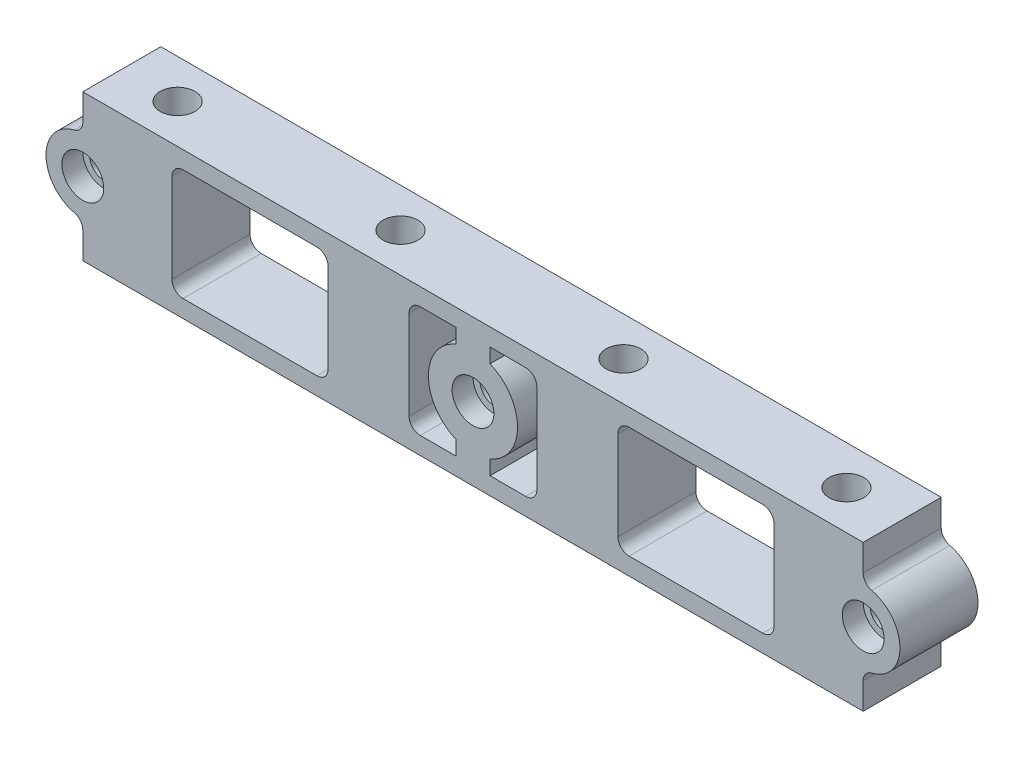
SolidWorks part; units mm, degrees
material "7075-T6 (SN)"
ref_plane "X-Y Datum" through (0, 0, 0) normal (0, 0, 1) x (1, 0, 0)
ref_plane "X-Z Datum" through (0, 0, 0) normal (0, 1, 0) x (1, 0, 0)
ref_plane "Y-Z Datum" through (0, 0, 0) normal (1, 0, 0) x (0, 0, -1)
other "Graphic1"
other "Graphic (Closed) -1"
other "Graphic2"
other "Graphic (Closed) -2"
other "Graphic3"
other "Graphic (Closed) -3"
sketch "Sketch1" plane through (0, 0, 0) normal (0, 0, 1) x (1, 0, 0)
  line L1 (8.7312, 16.6687) -> (-186.5312, 16.6687)
  line L5 (-8.7312, 0) -> (0, 0) construction
  line L7 (-186.5312, -16.6687) -> (-186.5312, 16.6687)
  line L8 (-8.7312, 0) -> (-16.6687, 0) construction
  line L9 (-8.7312, 0) -> (-8.7312, 16.6687) construction
  line L10 (-8.7312, 16.6687) -> (-16.6688, 16.6687) construction
  line L11 (-16.6687, 0) -> (-16.6688, 16.6687) construction
  line L12 (-67.4688, 0) -> (-59.5313, 0) construction
  line L13 (-67.4688, 0) -> (-67.4688, 16.6687) construction
  line L14 (-67.4688, 16.6687) -> (-59.5313, 16.6687) construction
  line L15 (-59.5313, 0) -> (-59.5313, 16.6687) construction
  line L17 (-186.5312, -16.6687) -> (8.7312, -16.6687)
  line L19 (8.7312, -16.6687) -> (8.7312, 16.6687)
  line L20 (-110.3313, 16.6687) -> (-118.2687, 16.6687) construction
  line L21 (-110.3313, 16.6687) -> (-110.3313, 0) construction
  line L22 (-110.3313, 0) -> (-118.2687, 0) construction
  line L23 (-118.2687, 16.6687) -> (-118.2687, 0) construction
  line L24 (-161.1313, 16.6687) -> (-169.0688, 16.6687) construction
  line L25 (-161.1313, 16.6687) -> (-161.1313, 0) construction
  line L26 (-161.1313, 0) -> (-169.0688, 0) construction
  line L27 (-169.0688, 16.6687) -> (-169.0688, 0) construction
  line L28 (0, 0) -> (8.7312, 0) construction
  line L29 (-177.8, 0) -> (-186.5312, 0) construction
  circle A0 centre (0, 0) radius 3.175
  circle A4 centre (-177.8, 0) radius 3.175
  circle A6 centre (-88.9, 0) radius 3.175
  point P1 (-186.5312, 0)
  point P22 (-12.7, 0)
  point P23 (-63.5, 0)
  point P31 (-114.3, 0)
  point P32 (-165.1, 0)
  point P38 (-88.9, -16.6687)
  dimension "D2" = 6.35
  dimension "D3" = 12.7
  dimension "D1" = 50.8
  dimension "D4" = 12.7
  dimension "D6" = 7.9375
  dimension "D7" = 7.9375
  dimension "D8" = 33.3375
  dimension "D11" = 50.8
  dimension "D12" = 50.8
extrude "Boss-Extrude1" add sketch "Sketch1" against normal blind 17.78
ref_plane "Plane1" through (0, 0, 0) normal (0, -1, 0) x (-1, 0, 0)
sketch "Sketch2" plane through (0, 16.6687, 0) normal (0, 1, 0) x (1, 0, 0)
  line L0 (-186.5312, 0) -> (8.7313, 0) construction
  line L4 (0, 0) -> (0, 17.78) construction
  line L5 (8.7313, 17.78) -> (-186.5312, 17.78) construction
  circle A0 centre (-12.7, 8.89) radius 3.9688
  circle A2 centre (-63.5, 8.89) radius 3.9688
  circle A3 centre (-114.3, 8.89) radius 3.9687
  circle A4 centre (-165.1, 8.89) radius 3.9688
  dimension "D2" = 7.9375
  dimension "D1" = 4
  dimension "D3" = 8.89
  dimension "D4" = 12.7
  dimension "D5" = 50.8
extrude "Cut-Extrude1" cut sketch "Sketch2" against normal up to surface (33.3375 mm away) up to face at (-88.9, -16.6687, -8.89)
sketch "Sketch3" plane through (0, 0, 0) normal (0, 0, 1) x (1, 0, 0)
  circle A0 centre (0, 0) radius 4.7625
  circle A1 centre (-88.9, 0) radius 4.7625
  circle A2 centre (-177.8, 0) radius 4.7625
  circle A3 centre (-177.8, 0) radius 3.175 construction
  dimension "D1" = 9.525
extrude "Cut-Extrude2" cut sketch "Sketch3" against normal blind 4.7752
ref_point "Point1"
ref_point "Point2"
ref_point "Point3"
ref_point "Point4"
sketch "Sketch5" plane through (0, 0, 0) normal (0, 0, 1) x (1, 0, 0)
  line L0 (0, -16.6687) -> (8.7312, -16.6687)
  line L1 (0, -10.6225) -> (0, -16.6687)
  line L2 (-186.5312, -16.6687) -> (8.7312, -16.6687) construction
  line L3 (0, 10.6225) -> (0, 16.6687)
  line L4 (8.7312, 16.6687) -> (-186.5312, 16.6687) construction
  line L5 (8.7312, -16.6687) -> (8.7312, 16.6687)
  line L6 (8.7312, 16.6687) -> (0, 16.6687)
  line L7 (-88.9, -16.6687) -> (-88.9, 16.6687) construction
  line L8 (0, 0) -> (-20.32, 0) construction
  line L9 (-22.86, -12.7) -> (-53.34, -12.7)
  line L10 (-20.32, -10.16) -> (-20.32, 10.16)
  line L11 (-22.86, 12.7) -> (-53.34, 12.7)
  line L12 (-55.88, -10.16) -> (-55.88, 10.16)
  line L13 (-85.0119, -9.3866) -> (-85.0119, -12.7)
  line L14 (-85.0119, -12.7) -> (-76.8839, -12.7)
  line L15 (-74.3439, -10.16) -> (-74.3439, 10.16)
  line L16 (-76.8839, 12.7) -> (-85.0119, 12.7)
  line L17 (-85.0119, 12.7) -> (-85.0119, 9.3866)
  line L18 (-88.9, 0) -> (-85.0119, -9.3866) construction
  line L19 (-88.9, 0) -> (-85.0119, 9.3866) construction
  line L20 (-100.9161, 12.7) -> (-92.7881, 12.7)
  line L21 (-103.4561, -10.16) -> (-103.4561, 10.16)
  line L22 (-92.7881, -12.7) -> (-100.9161, -12.7)
  line L23 (-92.7881, -9.3866) -> (-92.7881, -12.7)
  line L24 (-92.7881, 12.7) -> (-92.7881, 9.3866)
  line L25 (-154.94, 12.7) -> (-124.46, 12.7)
  line L26 (-121.92, -10.16) -> (-121.92, 10.16)
  line L27 (-154.94, -12.7) -> (-124.46, -12.7)
  line L28 (-157.48, -10.16) -> (-157.48, 10.16)
  line L29 (-186.5312, -16.6687) -> (-186.5312, 16.6687)
  line L30 (-177.8, -16.6687) -> (-186.5312, -16.6687)
  line L31 (-177.8, -10.6225) -> (-177.8, -16.6687)
  line L32 (-177.8, 10.6225) -> (-177.8, 16.6687)
  line L33 (-186.5312, 16.6687) -> (-177.8, 16.6687)
  arc A0 (1.9493, 8.1522) -> (1.9493, -8.1522) centre (0, 0) cw
  arc A1 (-85.0119, -9.3866) -> (-85.0119, 9.3866) centre (-88.9, 0) ccw
  arc A2 (0, -10.6225) -> (1.9493, -8.1522) centre (2.54, -10.6225) cw
  arc A3 (-22.86, 12.7) -> (-20.32, 10.16) centre (-22.86, 10.16) cw
  arc A4 (-55.88, 10.16) -> (-53.34, 12.7) centre (-53.34, 10.16) cw
  arc A5 (-55.88, -10.16) -> (-53.34, -12.7) centre (-53.34, -10.16) ccw
  arc A6 (0, 10.6225) -> (1.9493, 8.1522) centre (2.54, 10.6225) ccw
  arc A7 (-22.86, -12.7) -> (-20.32, -10.16) centre (-22.86, -10.16) ccw
  arc A8 (-92.7881, -9.3866) -> (-92.7881, 9.3866) centre (-88.9, 0) cw
  arc A9 (-121.92, 10.16) -> (-124.46, 12.7) centre (-124.46, 10.16) ccw
  arc A10 (-121.92, -10.16) -> (-124.46, -12.7) centre (-124.46, -10.16) cw
  arc A11 (-154.94, 12.7) -> (-157.48, 10.16) centre (-154.94, 10.16) ccw
  arc A12 (-154.94, -12.7) -> (-157.48, -10.16) centre (-154.94, -10.16) cw
  arc A13 (-177.8, -10.6225) -> (-179.7493, -8.1522) centre (-180.34, -10.6225) ccw
  arc A14 (-179.7493, 8.1522) -> (-179.7493, -8.1522) centre (-177.8, 0) ccw
  arc A15 (-177.8, 10.6225) -> (-179.7493, 8.1522) centre (-180.34, 10.6225) cw
  arc A16 (-103.4561, 10.16) -> (-100.9161, 12.7) centre (-100.9161, 10.16) cw
  arc A17 (-103.4561, -10.16) -> (-100.9161, -12.7) centre (-100.9161, -10.16) ccw
  arc A18 (-76.8839, 12.7) -> (-74.3439, 10.16) centre (-76.8839, 10.16) cw
  arc A19 (-76.8839, -12.7) -> (-74.3439, -10.16) centre (-76.8839, -10.16) ccw
  point P26 (0, -8.382)
  point P35 (-55.88, 12.7)
  point P38 (-55.88, -12.7)
  point P41 (0, 8.382)
  point P44 (-20.32, -12.7)
  point P76 (-103.4561, 12.7)
  point P79 (-103.4561, -12.7)
  point P82 (-74.3439, 12.7)
  point P85 (-74.3439, -12.7)
  dimension "D1" = 8.382
  dimension "D5" = 10.16
  dimension "D7" = 2.54
  dimension "D8" = 2.54
  dimension "D10" = 2.54
  dimension "D2" = 20.32
  dimension "D3" = 35.56
  dimension "D4" = 25.4
  dimension "D6" = 10.668
  dimension "D9" = 135
extrude "Cut-Extrude3" cut sketch "Sketch5" against normal up to surface (17.78 mm away) up to face at (-85.725, 0, -17.78)
